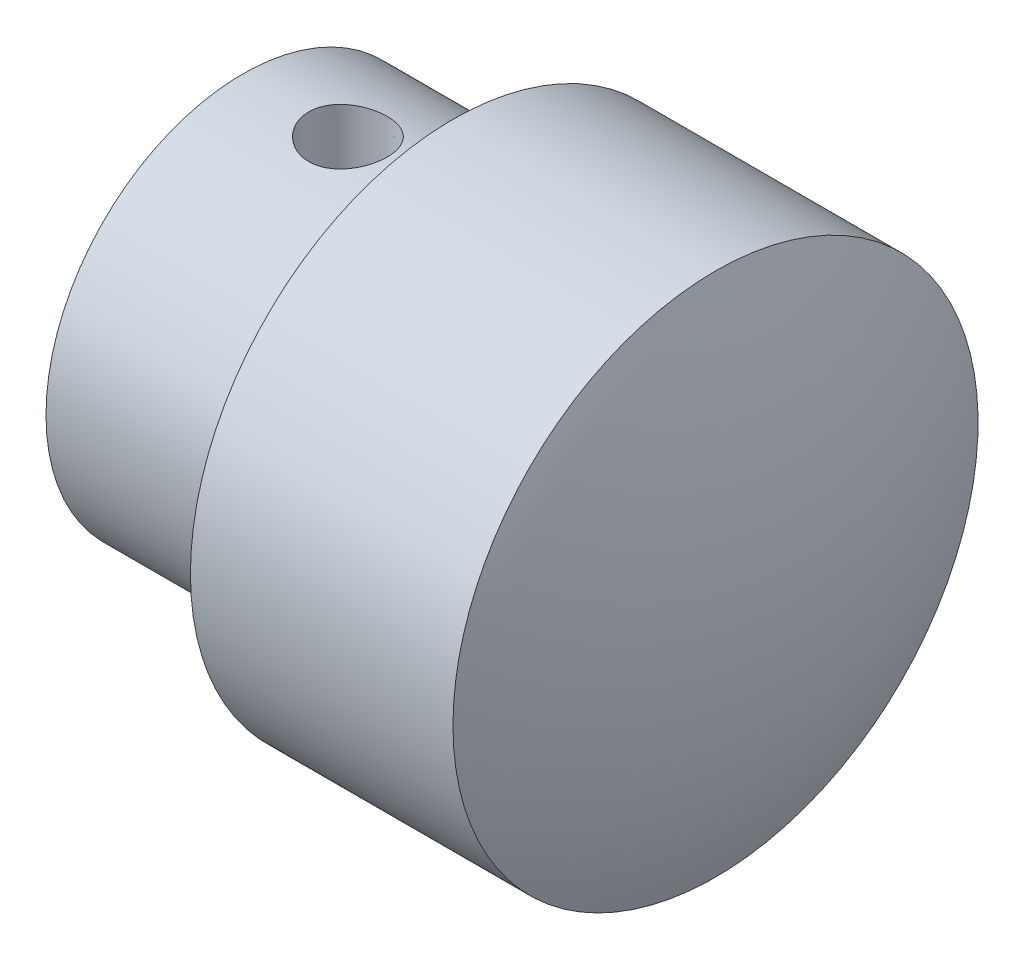
SolidWorks part; units mm, degrees
ref_plane "前视基准面" through (0, 0, 0) normal (0, 0, 1) x (1, 0, 0)
ref_plane "上视基准面" through (0, 0, 0) normal (0, 1, 0) x (1, 0, 0)
ref_plane "右视基准面" through (0, 0, 0) normal (1, 0, 0) x (0, 0, -1)
sketch "草图1" plane through (0, 0, 0) normal (0, 0, 1) x (1, 0, 0)
  line L0 (0, 0) -> (54.8107, 0) construction
  line L1 (55, 0) -> (-55, 0) construction
  line L2 (0, 0) -> (0, 7.5)
  line L3 (0, -55) -> (0, 55) construction
  line L4 (0, 7.5) -> (8, 7.5)
  line L5 (8, 7.5) -> (8, 10)
  line L6 (8, 10) -> (18, 10)
  line L7 (0, 0) -> (20.0871, 0)
  arc A0 (18, 10) -> (20.0871, 0) centre (-4.9129, 0) cw
  dimension "D1" = 25
  dimension "D2" = 18
  dimension "D3" = 8
  dimension "D4" = 20
  dimension "D5" = 15
revolve "旋转1" add sketch "草图1" angle 360 about L0
hole_wizard "Ø8.0mm 暗销孔1" positions "草图2" profile "草图3" hole size "Ø8.0" standard "GB"
sketch "草图2" plane through (0, 0, 0) normal (-1, 0, 0) x (0, 0, 1)
  point P0 (0, 0)
sketch "草图3" plane through (0, 0, 0) normal (0, 1, 0) x (0, 0, 1)
  line L0 (0, 0) -> (0, 10.4034)
  line L1 (0, 10.4034) -> (4, 8)
  line L2 (4, 8) -> (4, 0)
  line L5 (4, 0) -> (0, 0)
  line L10 (0, 10.4034) -> (-4, 8) construction
  line L11 (0, -6.35) -> (0, 107.95) construction
  dimension "孔直径" = 8
  dimension "孔深度" = 8
  dimension "导头角度" = 118
sketch "草图4" plane through (0, 0, 0) normal (0, 0, 1) x (1, 0, 0)
  line L0 (4, 18.564) -> (4, -26.2999) construction
  line L1 (0, -11) -> (0, 11) construction
  line L2 (4, -8.8951) -> (5.4, -8.8951)
  line L3 (5.4, -8.8951) -> (5.5, 8.7194)
  line L4 (5.5, 8.7194) -> (4, 8.7194)
  line L5 (4, -8.8951) -> (4, 8.7194)
  dimension "D1" = 4
  dimension "D2" = 1.5
  dimension "D3" = 2.8
revolve "切除-旋转1" cut sketch "草图4" angle 360 about L0
